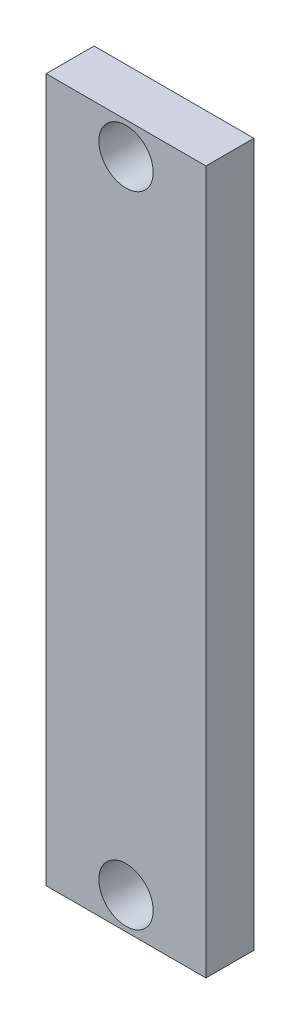
SolidWorks part; units mm, degrees
ref_plane "Front Plane" through (0, 0, 0) normal (0, 0, 1) x (1, 0, 0)
ref_plane "Top Plane" through (0, 0, 0) normal (0, 1, 0) x (1, 0, 0)
ref_plane "Right Plane" through (0, 0, 0) normal (1, 0, 0) x (0, 0, -1)
ref_plane "P_Front_87" through (0, 0, 87) normal (0, 0, 1) x (1, 0, 0)
sketch "Sketch1" plane through (0, 0, 87) normal (0, 0, 1) x (1, 0, 0)
  line L0 (-5, 20) -> (5, 20)
  line L1 (5, 20) -> (5, 64)
  line L2 (5, 64) -> (-5, 64)
  line L3 (-5, 64) -> (-5, 20)
extrude "Bar" add sketch "Sketch1" along normal blind 3
ref_plane "P_Front_86" through (0, 0, 86) normal (0, 0, 1) x (1, 0, 0)
sketch "Sketch2" plane through (0, 0, 86) normal (0, 0, 1) x (1, 0, 0)
  circle A0 centre (0, 62) radius 1.7
  circle A1 centre (0, 22) radius 1.7
extrude "M3_holes" cut sketch "Sketch2" along normal blind 5
